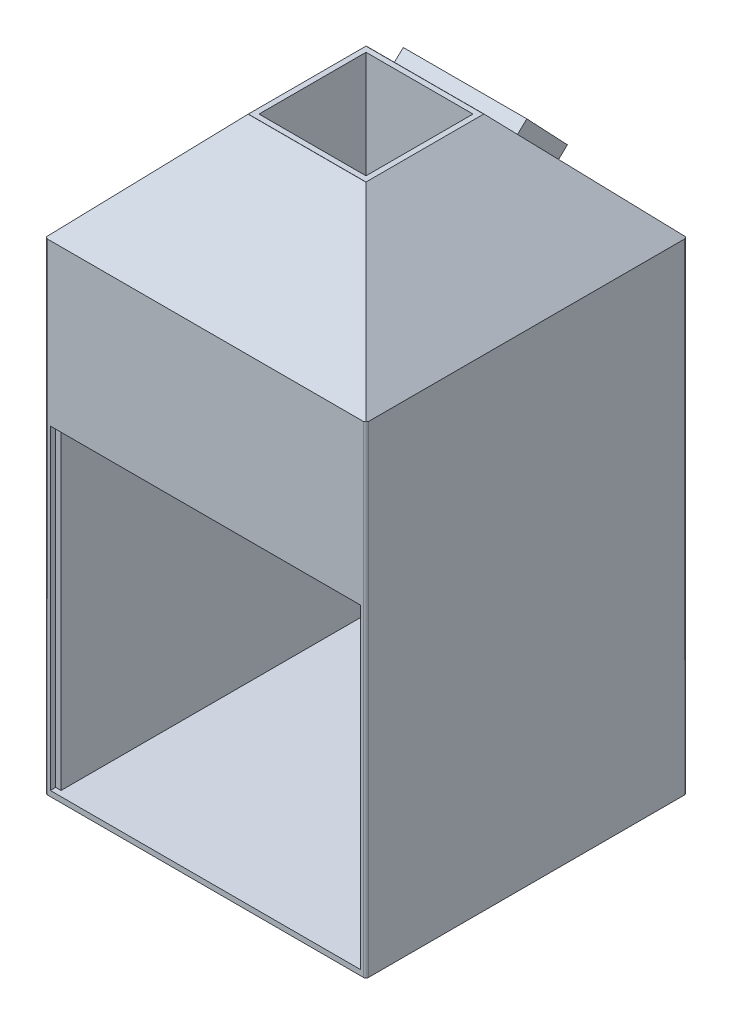
SolidWorks part; units mm, degrees
ref_plane "Front Plane" through (0, 0, 0) normal (0, 0, 1) x (1, 0, 0)
ref_plane "Top Plane" through (0, 0, 0) normal (0, 1, 0) x (1, 0, 0)
ref_plane "Right Plane" through (0, 0, 0) normal (1, 0, 0) x (0, 0, -1)
sketch "Sketch1" plane through (0, 0, 0) normal (0, 1, 0) x (1, 0, 0)
  line L1 (-300, 300) -> (300, 300)
  line L2 (-300, 300) -> (-300, -300)
  line L3 (-300, -300) -> (300, -300)
  line L4 (300, 300) -> (300, -300)
  line L5 (-300, 300) -> (300, -300) construction
  line L6 (-300, -300) -> (300, 300) construction
  point P0 (0, 0)
  dimension "D1" = 600
  dimension "D2" = 600
extrude "Boss-Extrude1" add sketch "Sketch1" along normal blind 10
sketch "Sketch2" plane through (0, 10, 0) normal (0, 1, 0) x (1, 0, 0)
  line L1 (-280, 280) -> (280, 280)
  line L2 (-280, 280) -> (-280, -280)
  line L3 (-280, -280) -> (280, -280)
  line L4 (300, -300) -> (300, 300)
  line L5 (300, 300) -> (-300, 300)
  line L6 (-300, 300) -> (-300, -300)
  line L7 (-300, -300) -> (300, -300)
  line L8 (300, -300) -> (300, 300)
  line L9 (300, 300) -> (-300, 300)
  line L10 (-300, 300) -> (-300, -300)
  line L11 (-300, -300) -> (300, -300)
  line L12 (280, 280) -> (280, -280)
  line L13 (-280, 280) -> (280, -280) construction
  line L14 (-280, -280) -> (280, 280) construction
  point P2 (0, 0)
  dimension "D2" = 20
  dimension "D3" = 20
  dimension "D1" = 0
extrude "Boss-Area C" add sketch "Sketch2" along normal blind 590
sketch "Sketch4" plane through (0, 600, 0) normal (0, 1, 0) x (1, 0, 0)
  line L0 (-300, -300) -> (300, -300) construction
  line L1 (-280, -300) -> (280, -300)
  line L2 (-280, -300) -> (-280, -280)
  line L3 (-280, -280) -> (280, -280)
  line L4 (280, -300) -> (280, -280)
  line L5 (0, -280) -> (0, -300) construction
  line L6 (-280, -290) -> (280, -290) construction
  point P352 (0, -290)
  dimension "D1" = 560
extrude "Cut-Area C" cut sketch "Sketch4" against normal blind 590
sketch "Sketch5" plane through (0, 600, 0) normal (0, 1, 0) x (1, 0, 0)
  line L0 (-300, -300) -> (300, -300)
  line L2 (-280, -280) -> (280, -280)
  line L10 (-300, -300) -> (-280, -300)
  line L11 (-280, -300) -> (-280, 280)
  line L12 (-280, 280) -> (280, 280)
  line L13 (280, 280) -> (280, -300)
  line L14 (280, -300) -> (300, -300)
  line L15 (300, -300) -> (300, 300)
  line L16 (300, 300) -> (-300, 300)
  line L17 (-300, 300) -> (-300, -300)
  line L18 (-300, -300) -> (-280, -300)
  line L19 (-280, -280) -> (-280, 280)
  line L20 (-280, 280) -> (280, 280)
  line L21 (280, 280) -> (280, -280)
  line L22 (280, -300) -> (300, -300)
  line M10 (-300, -300) -> (-280, -300)
  line M11 (-280, -300) -> (-280, 280)
  line M12 (-280, 280) -> (280, 280)
  line M13 (280, 280) -> (280, -300)
  line M14 (280, -300) -> (300, -300)
  line M15 (300, -300) -> (300, 300)
  line M16 (300, 300) -> (-300, 300)
  line M17 (-300, 300) -> (-300, -300)
  dimension "D1" = 0
  dimension "D2" = 20
extrude "Area B" add sketch "Sketch5" along normal blind 300 contours L2 L0 M11 M13 | M17 M10 M11 M12 M13 M14 M15 M16
sketch "Sketch7" plane through (0, 0, 300) normal (0, 0, 1) x (1, 0, 0)
  line L0 (280, 600) -> (290, 600)
  line L1 (-280, 600) -> (-290, 600)
  line L2 (0, 0) -> (0, 900) construction
  line L3 (-280, 10) -> (-290, 10)
  line L12 (-290, 10) -> (-290, 600)
  line L13 (280, 10) -> (290, 10)
  line L14 (290, 10) -> (290, 600)
  line L15 (-280, 600) -> (-280, 10)
  line L16 (280, 600) -> (280, 10)
  dimension "D2" = 10
extrude "Cut-Extrude3" cut sketch "Sketch7" against normal blind 10
ref_plane "Plane1" through (0, 1100, 0) normal (0, 1, 0) x (1, 0, 0)
sketch "Sketch8" plane through (0, 1100, 0) normal (0, 1, 0) x (1, 0, 0)
  line L1 (-100, 100) -> (100, 100)
  line L2 (-100, 100) -> (-100, -100)
  line L3 (-100, -100) -> (100, -100)
  line L4 (100, 100) -> (100, -100)
  line L5 (-100, 100) -> (100, -100) construction
  line L6 (-100, -100) -> (100, 100) construction
  line L7 (-110, 110) -> (110, 110)
  line L8 (-110, 110) -> (-110, -110)
  line L9 (-110, -110) -> (110, -110)
  line L10 (110, 110) -> (110, -110)
  line L11 (-110, 110) -> (110, -110) construction
  line L12 (-110, -110) -> (110, 110) construction
  point P0 (0, 0)
  point P6 (0, 0)
  dimension "D1" = 200
  dimension "D2" = 200
  dimension "D3" = 220
  dimension "D4" = 220
extrude "Boss-Extrude7" add sketch "Sketch8" against normal blind 210 separate body
sketch "Sketch9" plane through (0, 0, -300) normal (0, 0, -1) x (-1, 0, 0)
  line L0 (110, 1100) -> (110, 1090)
  line L1 (330, 1100) -> (-330, 1100) construction
  line L2 (110, 890) -> (110, 1100) construction
  line L3 (290, 900) -> (300, 900)
  line L4 (-300, 0) -> (300, 0)
  line L5 (300, 0) -> (300, 900)
  line L6 (300, 900) -> (-300, 900)
  line L7 (-300, 900) -> (-300, 0)
  line L10 (300, 900) -> (290, 900)
  line L12 (110, 1100) -> (300, 900)
  line L13 (110, 1100) -> (110, 1090)
  line L14 (110, 1090) -> (290, 900)
  line L15 (290, 900) -> (300, 900)
  line L16 (0, 0) -> (0, 1100) construction
  line L17 (-290, 900) -> (-300, 900)
  line L18 (-110, 1100) -> (-110, 1090)
  line L19 (-110, 1090) -> (-290, 900)
  line L20 (-110, 1100) -> (-300, 900)
  line M11 (300, 900) -> (-300, 900)
  dimension "D2" = 10
  dimension "D3" = 10
  dimension "D1" = 0
extrude "Boss-Extrude8" add sketch "Sketch9" against normal blind 600 contours L0 L14 L12 M11
ref_plane "Plane2" through (0, 0, 0) normal (1, 0, 0) x (0, 0, -1)
mirror "Mirror1" about plane through (0, 0, 0) normal (1, 0, 0) of "Boss-Extrude8"
sketch "Sketch10" plane through (-300, 0, 0) normal (-1, 0, 0) x (0, 0, 1)
  line L0 (-300, 900) -> (-300, 1100)
  line L1 (-300, 1100) -> (-110, 1100)
  line L2 (-110, 1100) -> (-300, 900)
  line L3 (0, 0) -> (0, 1100) construction
  line L4 (-300, 0) -> (300, 0) construction
  line L5 (-110, 1100) -> (110, 1100) construction
  line L6 (300, 1100) -> (110, 1100)
  line L7 (300, 900) -> (300, 1100)
  line L8 (110, 1100) -> (300, 900)
extrude "Cut-Extrude4" cut sketch "Sketch10" against normal blind 600
sketch "Sketch13" plane through (300, 0, 0) normal (1, 0, 0) x (0, 0, -1)
  line L0 (-300, 900) -> (-290, 900)
  line L1 (-300, 900) -> (300, 900) construction
  line L2 (-290, 900) -> (-110.3155, 1090)
  line L3 (319, 1100) -> (-319, 1100) construction
  line L5 (-110.3155, 1100) -> (-300, 900)
  line L6 (0, 0) -> (0, 1100) construction
  line L7 (-110.3155, 1100) -> (-110.3155, 1090)
  line L8 (300, 900) -> (290, 900)
  line L9 (110.3155, 1100) -> (110.3155, 1090)
  line L10 (290, 900) -> (110.3155, 1090)
  line L11 (110.3155, 1100) -> (300, 900)
  dimension "D1" = 10
  dimension "D2" = 10
extrude "Boss-Extrude9" add sketch "Sketch13" against normal blind 600
sketch "Sketch14" plane through (0, 0, -300) normal (0, 0, -1) x (-1, 0, 0)
  line L1 (0, 110) -> (0, -110) construction
  line L3 (319, 1100) -> (-319, 1100) construction
  line L4 (-110, 1100) -> (-300, 900)
  line L5 (-300, 900) -> (-300, 1100)
  line L6 (-300, 1100) -> (-110, 1100)
  line L7 (300, 1100) -> (110, 1100)
  line L8 (300, 900) -> (300, 1100)
  line L9 (110, 1100) -> (300, 900)
  dimension "D1" = 190
extrude "Cut-Extrude5" cut sketch "Sketch14" against normal blind 600
sketch "Sketch16" plane through (0, 575.9823, -607.3057) normal (0, 0.6881, -0.7256) x (-1, 0, 0)
  line L0 (0, 723.0441) -> (0, 446.5694) construction
  line L1 (0, 110) -> (0, -110) construction
  line L2 (-300, 446.5694) -> (300, 446.5694) construction
  line L4 (-115.5, 639.8067) -> (115.5, 639.8067)
  line L5 (-115.5, 639.8067) -> (-115.5, 529.8067)
  line L6 (-115.5, 529.8067) -> (115.5, 529.8067)
  line L7 (115.5, 639.8067) -> (115.5, 529.8067)
  line L8 (-115.5, 639.8067) -> (115.5, 529.8067) construction
  line L9 (-115.5, 529.8067) -> (115.5, 639.8067) construction
  line L10 (-105, 634.8067) -> (105, 634.8067)
  line L11 (-105, 634.8067) -> (-105, 534.8067)
  line L12 (-105, 534.8067) -> (105, 534.8067)
  line L13 (105, 634.8067) -> (105, 534.8067)
  line L14 (-105, 634.8067) -> (105, 534.8067) construction
  line L15 (-105, 534.8067) -> (105, 634.8067) construction
  point P6 (0, 584.8067)
  point P11 (0, 584.8067)
  dimension "D1" = 110
  dimension "D2" = 100
  dimension "D3" = 210
  dimension "D4" = 231
extrude "Boss-Extrude13" add sketch "Sketch16" along normal blind 25
sketch "Sketch18" plane through (0, 575.9823, -607.3057) normal (0, 0.6881, -0.7256) x (-1, 0, 0)
  line L0 (0, 634.8067) -> (0, 534.8067) construction
  line L1 (105, 634.8067) -> (-105, 634.8067) construction
  line L2 (-105, 534.8067) -> (105, 534.8067) construction
  line L3 (-105, 584.8067) -> (105, 584.8067) construction
  line L4 (-105, 634.8067) -> (-105, 534.8067) construction
  line L5 (105, 534.8067) -> (105, 634.8067) construction
  circle A1 centre (-35, 584.8067) radius 10
  circle A2 centre (35, 584.8067) radius 10
  dimension "D2" = 20
extrude "Cut-Extrude6" cut sketch "Sketch18" against normal blind 35
fillet "Fillet1" radius 5 4 edges at (300, 450, 300) (-300, 450, 300) (-300, 450, -300) (300, 450, -300)
